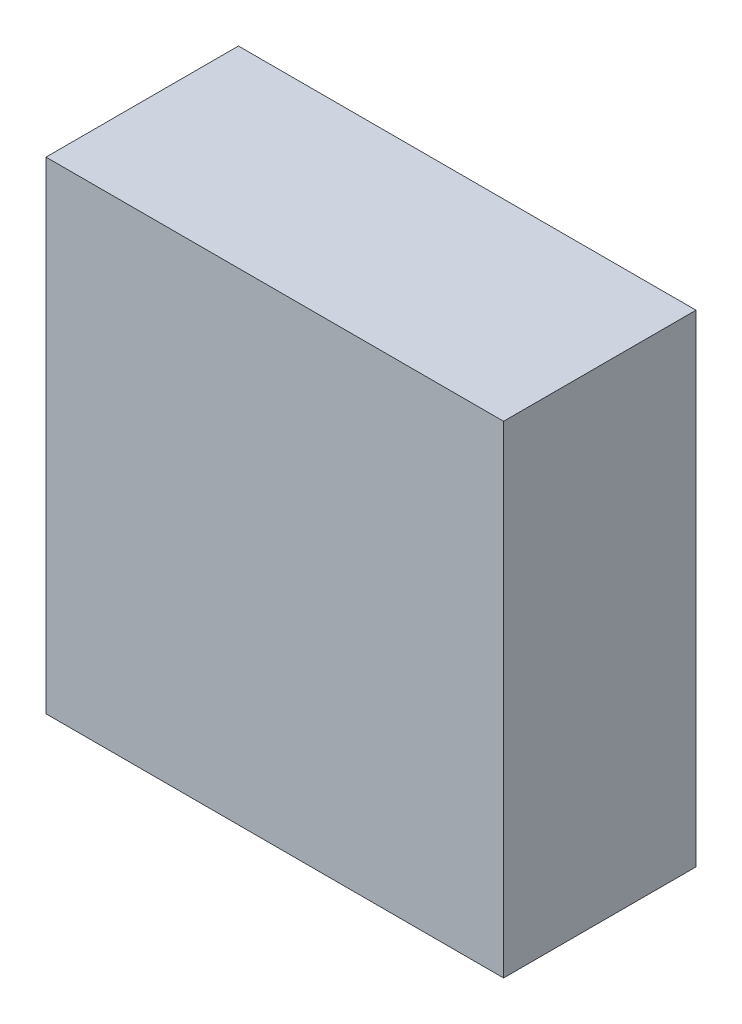
SolidWorks part; units mm, degrees
ref_plane "Front Plane" through (0, 0, 0) normal (0, 0, 1) x (1, 0, 0)
ref_plane "Top Plane" through (0, 0, 0) normal (0, 1, 0) x (1, 0, 0)
ref_plane "Right Plane" through (0, 0, 0) normal (1, 0, 0) x (0, 0, -1)
sketch "Sketch1" plane through (0, 0, 0) normal (0, 0, 1) x (1, 0, 0)
  line L0 (-8.7364, 4.953) -> (0.6592, 4.953)
  line L1 (0.6592, 4.953) -> (0.6592, -4.947)
  line L2 (0.6592, -4.947) -> (-8.7364, -4.947)
  line L3 (-8.7364, -4.947) -> (-8.7364, 4.953)
extrude "Component_Outline" add sketch "Sketch1" along normal blind 3.9509 separate body
sketch3d "3DSketch1"
  line L0 (0, 0, 0) -> (1, 0, 0)
  line L1 (0, 0, 0) -> (0, 1, 0)
  line L2 (0, 0, 0) -> (0, 0, 1)
  point P0 (0, 0, 0)
